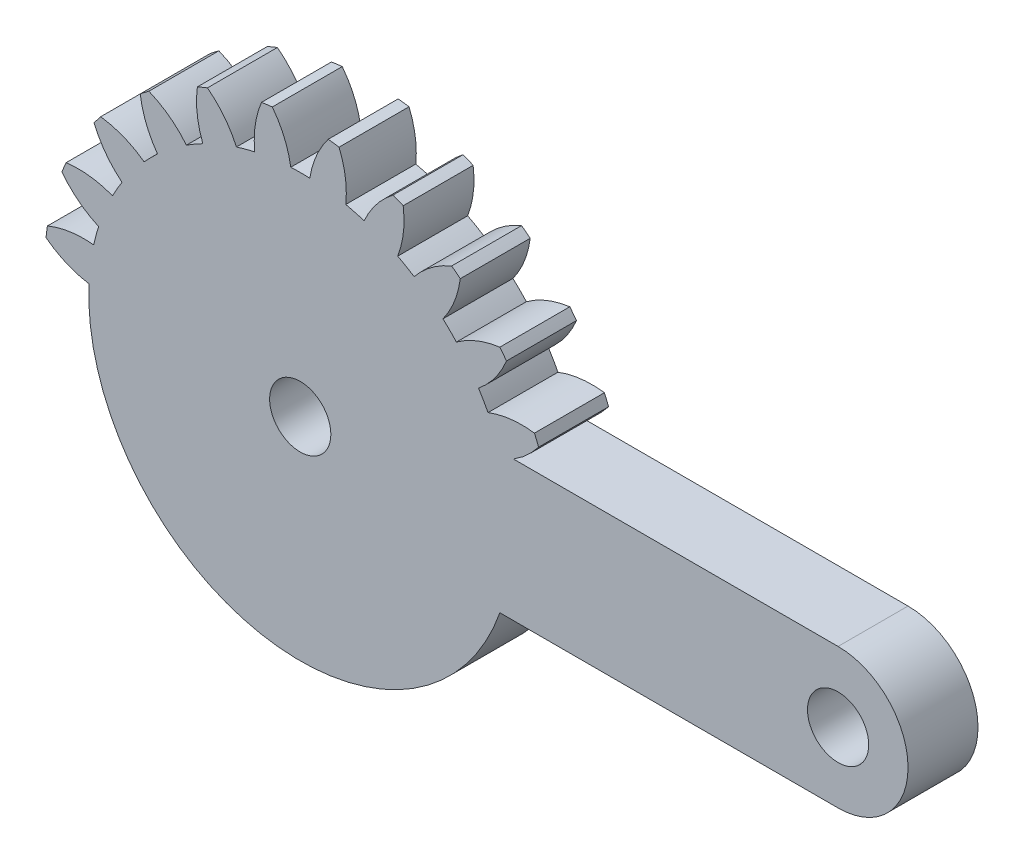
SolidWorks part; units mm, degrees
ref_plane "Front Plane" through (0, 0, 0) normal (0, 0, 1) x (1, 0, 0)
ref_plane "Top Plane" through (0, 0, 0) normal (0, 1, 0) x (1, 0, 0)
ref_plane "Right Plane" through (0, 0, 0) normal (1, 0, 0) x (0, 0, -1)
sketch "Sketch1" plane through (0, 0, 0) normal (0, 0, 1) x (1, 0, 0)
  line L0 (20.64, 4) -> (2.08, 4)
  line L1 (20.64, -4) -> (2.08, -4)
  circle A0 centre (-10.11, 0) radius 1.75
  circle A1 centre (20.64, 0) radius 1.75
  arc A2 (20.64, -4) -> (20.64, 4) centre (20.64, 0) ccw
  arc A6 (2.08, 4) -> (3.5201, 5.3071) centre (-0.7699, 8.5867) ccw
  arc A7 (3.5201, 5.3071) -> (3.2812, 5.8838) centre (-10.108, 0) ccw
  arc A8 (3.2812, 5.8838) -> (0.6255, 5.5703) centre (2.5667, 0.5313) ccw
  arc A9 (0.6255, 5.5703) -> (0.0827, 6.5103) centre (-10.108, 0) ccw
  arc A10 (0.0827, 6.5103) -> (1.6822, 8.6535) centre (-3.3105, 10.711) ccw
  arc A11 (1.6822, 8.6535) -> (1.3022, 9.1487) centre (-10.108, 0) ccw
  arc A12 (1.3022, 9.1487) -> (-1.182, 8.1585) centre (1.9973, 3.7936) ccw
  arc A13 (-1.182, 8.1585) -> (-1.9495, 8.926) centre (-10.108, 0) ccw
  arc A14 (-1.9495, 8.926) -> (-0.9593, 11.4102) centre (-6.3143, 12.1053) ccw
  arc A15 (-0.9593, 11.4102) -> (-1.4545, 11.7901) centre (-10.108, 0) ccw
  arc A16 (-1.4545, 11.7901) -> (-3.5977, 10.1907) centre (0.603, 6.7975) ccw
  arc A17 (-3.5977, 10.1907) -> (-4.5377, 10.7334) centre (-10.108, 0) ccw
  arc A18 (-4.5377, 10.7334) -> (-4.2242, 13.3892) centre (-9.5767, 12.6747) ccw
  arc A19 (-4.2242, 13.3892) -> (-4.8008, 13.6281) centre (-10.108, 0) ccw
  arc A20 (-4.8008, 13.6281) -> (-6.4571, 11.5285) centre (-1.5213, 9.3381) ccw
  arc A21 (-6.4571, 11.5285) -> (-7.5055, 11.8094) centre (-10.108, 0) ccw
  arc A22 (-7.5055, 11.8094) -> (-7.8901, 14.4558) centre (-12.8753, 12.3803) ccw
  arc A23 (-7.8901, 14.4558) -> (-8.5089, 14.5373) centre (-10.108, 0) ccw
  arc A24 (-8.5089, 14.5373) -> (-9.5653, 12.0806) centre (-4.2307, 11.2423) ccw
  arc A25 (-9.5653, 12.0806) -> (-10.6507, 12.0806) centre (-10.108, 0) ccw
  arc A26 (-10.6507, 12.0806) -> (-11.7071, 14.5373) centre (-15.9852, 11.2423) ccw
  arc A27 (-11.7071, 14.5373) -> (-12.3259, 14.4558) centre (-10.108, 0) ccw
  arc A28 (-12.3259, 14.4558) -> (-12.7104, 11.8094) centre (-7.3407, 12.3803) ccw
  arc A29 (-12.7104, 11.8094) -> (-13.7589, 11.5285) centre (-10.108, 0) ccw
  arc A30 (-13.7589, 11.5285) -> (-15.4151, 13.6281) centre (-18.6947, 9.3381) ccw
  arc A31 (-15.4151, 13.6281) -> (-15.9918, 13.3892) centre (-10.108, 0) ccw
  arc A32 (-15.9918, 13.3892) -> (-15.6783, 10.7334) centre (-10.6393, 12.6747) ccw
  arc A33 (-15.6783, 10.7334) -> (-16.6183, 10.1907) centre (-10.108, 0) ccw
  arc A34 (-16.6183, 10.1907) -> (-18.7615, 11.7901) centre (-20.819, 6.7975) ccw
  arc A35 (-18.7615, 11.7901) -> (-19.2567, 11.4102) centre (-10.108, 0) ccw
  arc A36 (-19.2567, 11.4102) -> (-18.2665, 8.926) centre (-13.9016, 12.1053) ccw
  arc A37 (-18.2665, 8.926) -> (-19.034, 8.1585) centre (-10.108, 0) ccw
  arc A38 (-19.034, 8.1585) -> (-21.5181, 9.1487) centre (-22.2133, 3.7936) ccw
  arc A39 (-21.5181, 9.1487) -> (-21.8981, 8.6535) centre (-10.108, 0) ccw
  arc A40 (-21.8981, 8.6535) -> (-20.2987, 6.5103) centre (-16.9054, 10.711) ccw
  arc A41 (-20.2987, 6.5103) -> (-20.8414, 5.5703) centre (-10.108, 0) ccw
  arc A42 (-20.8414, 5.5703) -> (-23.4972, 5.8838) centre (-22.7827, 0.5313) ccw
  arc A43 (-23.4972, 5.8838) -> (-23.7361, 5.3071) centre (-10.108, 0) ccw
  arc A44 (-23.7361, 5.3071) -> (-21.6364, 3.6509) centre (-19.446, 8.5867) ccw
  arc A45 (-21.6364, 3.6509) -> (-21.9174, 2.6025) centre (-10.108, 0) ccw
  arc A46 (-21.9174, 2.6025) -> (-24.5638, 2.2179) centre (-22.4883, -2.7673) ccw
  arc A47 (-24.5638, 2.2179) -> (-24.6453, 1.5991) centre (-10.108, 0) ccw
  arc A48 (-24.6453, 1.5991) -> (-22.1885, 0.5427) centre (-21.3503, 5.8773) ccw
  arc A49 (-22.1885, 0.5427) -> (-22.1885, -0.5427) centre (-10.108, 0) ccw
  arc A50 (-22.1885, -0.5427) -> (-24.6453, -1.5991) centre (-21.3503, -5.8773) ccw
  arc A51 (-24.6453, -1.5991) -> (-24.5638, -2.2179) centre (-10.108, 0) ccw
  arc A52 (-24.5638, -2.2179) -> (-21.9174, -2.6025) centre (-22.4883, 2.7673) ccw
  arc A53 (-21.9174, -2.6025) -> (-21.6364, -3.6509) centre (-10.108, 0) ccw
  arc A54 (-21.6364, -3.6509) -> (-23.7361, -5.3071) centre (-19.446, -8.5867) ccw
  arc A55 (-23.7361, -5.3071) -> (-23.4972, -5.8838) centre (-10.108, 0) ccw
  arc A56 (-23.4972, -5.8838) -> (-20.8414, -5.5703) centre (-22.7827, -0.5313) ccw
  arc A57 (-20.8414, -5.5703) -> (-20.2987, -6.5103) centre (-10.108, 0) ccw
  arc A58 (-20.2987, -6.5103) -> (-21.8981, -8.6535) centre (-16.9054, -10.711) ccw
  arc A59 (-21.8981, -8.6535) -> (-21.5181, -9.1487) centre (-10.108, 0) ccw
  arc A60 (-21.5181, -9.1487) -> (-19.034, -8.1585) centre (-22.2133, -3.7936) ccw
  arc A61 (-19.034, -8.1585) -> (-18.2665, -8.926) centre (-10.108, 0) ccw
  arc A62 (-18.2665, -8.926) -> (-19.2567, -11.4102) centre (-13.9016, -12.1053) ccw
  arc A63 (-19.2567, -11.4102) -> (-18.7615, -11.7901) centre (-10.108, 0) ccw
  arc A64 (-18.7615, -11.7901) -> (-16.6183, -10.1907) centre (-20.819, -6.7975) ccw
  arc A65 (-16.6183, -10.1907) -> (-15.6783, -10.7334) centre (-10.108, 0) ccw
  arc A66 (-15.6783, -10.7334) -> (-15.9918, -13.3892) centre (-10.6393, -12.6747) ccw
  arc A67 (-15.9918, -13.3892) -> (-15.4151, -13.6281) centre (-10.108, 0) ccw
  arc A68 (-15.4151, -13.6281) -> (-13.7589, -11.5285) centre (-18.6947, -9.3381) ccw
  arc A69 (-13.7589, -11.5285) -> (-12.7104, -11.8094) centre (-10.108, 0) ccw
  arc A70 (-12.7104, -11.8094) -> (-12.3259, -14.4558) centre (-7.3407, -12.3803) ccw
  arc A71 (-12.3259, -14.4558) -> (-11.7071, -14.5373) centre (-10.108, 0) ccw
  arc A72 (-11.7071, -14.5373) -> (-10.6507, -12.0806) centre (-15.9852, -11.2423) ccw
  arc A73 (-10.6507, -12.0806) -> (-9.5653, -12.0806) centre (-10.108, 0) ccw
  arc A74 (-9.5653, -12.0806) -> (-8.5089, -14.5373) centre (-4.2307, -11.2423) ccw
  arc A75 (-8.5089, -14.5373) -> (-7.8901, -14.4558) centre (-10.108, 0) ccw
  arc A76 (-7.8901, -14.4558) -> (-7.5055, -11.8094) centre (-12.8753, -12.3803) ccw
  arc A77 (-7.5055, -11.8094) -> (-6.4571, -11.5285) centre (-10.108, 0) ccw
  arc A78 (-6.4571, -11.5285) -> (-4.8008, -13.6281) centre (-1.5213, -9.3381) ccw
  arc A79 (-4.8008, -13.6281) -> (-4.2242, -13.3892) centre (-10.108, 0) ccw
  arc A80 (-4.2242, -13.3892) -> (-4.5377, -10.7334) centre (-9.5767, -12.6747) ccw
  arc A81 (-4.5377, -10.7334) -> (-3.5977, -10.1907) centre (-10.108, 0) ccw
  arc A82 (-3.5977, -10.1907) -> (-1.4545, -11.7901) centre (0.603, -6.7975) ccw
  arc A83 (-1.4545, -11.7901) -> (-0.9593, -11.4102) centre (-10.108, 0) ccw
  arc A84 (-0.9593, -11.4102) -> (-1.9495, -8.926) centre (-6.3143, -12.1053) ccw
  arc A85 (-1.9495, -8.926) -> (-1.182, -8.1585) centre (-10.108, 0) ccw
  arc A86 (-1.182, -8.1585) -> (1.3022, -9.1487) centre (1.9973, -3.7936) ccw
  arc A87 (1.3022, -9.1487) -> (1.6822, -8.6535) centre (-10.108, 0) ccw
  arc A88 (1.6822, -8.6535) -> (0.0827, -6.5103) centre (-3.3105, -10.711) ccw
  arc A89 (0.0827, -6.5103) -> (0.6255, -5.5703) centre (-10.108, 0) ccw
  arc A90 (0.6255, -5.5703) -> (3.2812, -5.8838) centre (2.5667, -0.5313) ccw
  arc A91 (3.2812, -5.8838) -> (3.5201, -5.3071) centre (-10.108, 0) ccw
  arc A92 (3.5201, -5.3071) -> (2.08, -4) centre (-0.7699, -8.5867) ccw
  dimension "D1" = 3.5
  dimension "D4" = 8
  dimension "D6" = 5.4
  dimension "D7" = 5.4
  dimension "D2" = 10.11
  dimension "D3" = 20.64
  dimension "D5" = 18.56
extrude "Boss-Extrude1" add sketch "Sketch1" along normal blind 4
sketch "Sketch2" plane through (0, 0, 4) normal (0, 0, 1) x (1, 0, 0)
  line L2 (20.64, 4) -> (2.08, 4)
  line L3 (2.08, -4) -> (20.64, -4)
  line L4 (20.64, 4) -> (2.08, 4)
  line L5 (1.3041, -4) -> (20.64, -4)
  arc A88 (20.64, -4) -> (20.64, 4) centre (20.64, 0) ccw
  arc A89 (2.08, 4) -> (3.5201, 5.3071) centre (-0.7699, 8.5867) ccw
  arc A90 (3.5201, 5.3071) -> (3.2812, 5.8838) centre (-10.108, 0) ccw
  arc A91 (3.2812, 5.8838) -> (0.6255, 5.5703) centre (2.5667, 0.5313) ccw
  arc A92 (0.6255, 5.5703) -> (0.0827, 6.5103) centre (-10.108, 0) ccw
  arc A93 (0.0827, 6.5103) -> (1.6822, 8.6535) centre (-3.3105, 10.711) ccw
  arc A94 (1.6822, 8.6535) -> (1.3022, 9.1487) centre (-10.108, 0) ccw
  arc A95 (1.3022, 9.1487) -> (-1.182, 8.1585) centre (1.9973, 3.7936) ccw
  arc A96 (-1.182, 8.1585) -> (-1.9495, 8.926) centre (-10.108, 0) ccw
  arc A97 (-1.9495, 8.926) -> (-0.9593, 11.4102) centre (-6.3143, 12.1053) ccw
  arc A98 (-0.9593, 11.4102) -> (-1.4545, 11.7901) centre (-10.108, 0) ccw
  arc A99 (-1.4545, 11.7901) -> (-3.5977, 10.1907) centre (0.603, 6.7975) ccw
  arc A100 (-3.5977, 10.1907) -> (-4.5377, 10.7334) centre (-10.108, 0) ccw
  arc A101 (-4.5377, 10.7334) -> (-4.2242, 13.3892) centre (-9.5767, 12.6747) ccw
  arc A102 (-4.2242, 13.3892) -> (-4.8008, 13.6281) centre (-10.108, 0) ccw
  arc A103 (-4.8008, 13.6281) -> (-6.4571, 11.5285) centre (-1.5213, 9.3381) ccw
  arc A104 (-6.4571, 11.5285) -> (-7.5055, 11.8094) centre (-10.108, 0) ccw
  arc A105 (-7.5055, 11.8094) -> (-7.8901, 14.4558) centre (-12.8753, 12.3803) ccw
  arc A106 (-7.8901, 14.4558) -> (-8.5089, 14.5373) centre (-10.108, 0) ccw
  arc A107 (-8.5089, 14.5373) -> (-9.5653, 12.0806) centre (-4.2307, 11.2423) ccw
  arc A108 (-9.5653, 12.0806) -> (-10.6507, 12.0806) centre (-10.108, 0) ccw
  arc A109 (-10.6507, 12.0806) -> (-11.7071, 14.5373) centre (-15.9852, 11.2423) ccw
  arc A110 (-11.7071, 14.5373) -> (-12.3259, 14.4558) centre (-10.108, 0) ccw
  arc A111 (-12.3259, 14.4558) -> (-12.7104, 11.8094) centre (-7.3407, 12.3803) ccw
  arc A112 (-12.7104, 11.8094) -> (-13.7589, 11.5285) centre (-10.108, 0) ccw
  arc A113 (-13.7589, 11.5285) -> (-15.4151, 13.6281) centre (-18.6947, 9.3381) ccw
  arc A114 (-15.4151, 13.6281) -> (-15.9918, 13.3892) centre (-10.108, 0) ccw
  arc A115 (-15.9918, 13.3892) -> (-15.6783, 10.7334) centre (-10.6393, 12.6747) ccw
  arc A116 (-15.6783, 10.7334) -> (-16.6183, 10.1907) centre (-10.108, 0) ccw
  arc A117 (-16.6183, 10.1907) -> (-18.7615, 11.7901) centre (-20.819, 6.7975) ccw
  arc A118 (-18.7615, 11.7901) -> (-19.2567, 11.4102) centre (-10.108, 0) ccw
  arc A119 (-19.2567, 11.4102) -> (-18.2665, 8.926) centre (-13.9016, 12.1053) ccw
  arc A120 (-18.2665, 8.926) -> (-19.034, 8.1585) centre (-10.108, 0) ccw
  arc A121 (-19.034, 8.1585) -> (-21.5181, 9.1487) centre (-22.2133, 3.7936) ccw
  arc A122 (-21.5181, 9.1487) -> (-21.8981, 8.6535) centre (-10.108, 0) ccw
  arc A123 (-21.8981, 8.6535) -> (-20.2987, 6.5103) centre (-16.9054, 10.711) ccw
  arc A124 (-20.2987, 6.5103) -> (-20.8414, 5.5703) centre (-10.108, 0) ccw
  arc A125 (-20.8414, 5.5703) -> (-23.4972, 5.8838) centre (-22.7827, 0.5313) ccw
  arc A126 (-23.4972, 5.8838) -> (-23.7361, 5.3071) centre (-10.108, 0) ccw
  arc A127 (-23.7361, 5.3071) -> (-21.6364, 3.6509) centre (-19.446, 8.5867) ccw
  arc A128 (-21.6364, 3.6509) -> (-21.9174, 2.6025) centre (-10.108, 0) ccw
  arc A129 (-21.9174, 2.6025) -> (-24.5638, 2.2179) centre (-22.4883, -2.7673) ccw
  arc A130 (-24.5638, 2.2179) -> (-24.6453, 1.5991) centre (-10.108, 0) ccw
  arc A131 (-24.6453, 1.5991) -> (-22.1885, 0.5427) centre (-21.3503, 5.8773) ccw
  arc A132 (-22.1885, 0.5427) -> (-22.1885, -0.5427) centre (-10.108, 0) ccw
  arc A133 (-22.1885, -0.5427) -> (-24.6453, -1.5991) centre (-21.3503, -5.8773) ccw
  arc A134 (-24.6453, -1.5991) -> (-24.5638, -2.2179) centre (-10.108, 0) ccw
  arc A135 (-24.5638, -2.2179) -> (-21.9174, -2.6025) centre (-22.4883, 2.7673) ccw
  arc A136 (-21.9174, -2.6025) -> (-21.6364, -3.6509) centre (-10.108, 0) ccw
  arc A137 (-21.6364, -3.6509) -> (-23.7361, -5.3071) centre (-19.446, -8.5867) ccw
  arc A138 (-23.7361, -5.3071) -> (-23.4972, -5.8838) centre (-10.108, 0) ccw
  arc A139 (-23.4972, -5.8838) -> (-20.8414, -5.5703) centre (-22.7827, -0.5313) ccw
  arc A140 (-20.8414, -5.5703) -> (-20.2987, -6.5103) centre (-10.108, 0) ccw
  arc A141 (-20.2987, -6.5103) -> (-21.8981, -8.6535) centre (-16.9054, -10.711) ccw
  arc A142 (-21.8981, -8.6535) -> (-21.5181, -9.1487) centre (-10.108, 0) ccw
  arc A143 (-21.5181, -9.1487) -> (-19.034, -8.1585) centre (-22.2133, -3.7936) ccw
  arc A144 (-19.034, -8.1585) -> (-18.2665, -8.926) centre (-10.108, 0) ccw
  arc A145 (-18.2665, -8.926) -> (-19.2567, -11.4102) centre (-13.9016, -12.1053) ccw
  arc A146 (-19.2567, -11.4102) -> (-18.7615, -11.7901) centre (-10.108, 0) ccw
  arc A147 (-18.7615, -11.7901) -> (-16.6183, -10.1907) centre (-20.819, -6.7975) ccw
  arc A148 (-16.6183, -10.1907) -> (-15.6783, -10.7334) centre (-10.108, 0) ccw
  arc A149 (-15.6783, -10.7334) -> (-15.9918, -13.3892) centre (-10.6393, -12.6747) ccw
  arc A150 (-15.9918, -13.3892) -> (-15.4151, -13.6281) centre (-10.108, 0) ccw
  arc A151 (-15.4151, -13.6281) -> (-13.7589, -11.5285) centre (-18.6947, -9.3381) ccw
  arc A152 (-13.7589, -11.5285) -> (-12.7104, -11.8094) centre (-10.108, 0) ccw
  arc A153 (-12.7104, -11.8094) -> (-12.3259, -14.4558) centre (-7.3407, -12.3803) ccw
  arc A154 (-12.3259, -14.4558) -> (-11.7071, -14.5373) centre (-10.108, 0) ccw
  arc A155 (-11.7071, -14.5373) -> (-10.6507, -12.0806) centre (-15.9852, -11.2423) ccw
  arc A156 (-10.6507, -12.0806) -> (-9.5653, -12.0806) centre (-10.108, 0) ccw
  arc A157 (-9.5653, -12.0806) -> (-8.5089, -14.5373) centre (-4.2307, -11.2423) ccw
  arc A158 (-8.5089, -14.5373) -> (-7.8901, -14.4558) centre (-10.108, 0) ccw
  arc A159 (-7.8901, -14.4558) -> (-7.5055, -11.8094) centre (-12.8753, -12.3803) ccw
  arc A160 (-7.5055, -11.8094) -> (-6.4571, -11.5285) centre (-10.108, 0) ccw
  arc A161 (-6.4571, -11.5285) -> (-4.8008, -13.6281) centre (-1.5213, -9.3381) ccw
  arc A162 (-4.8008, -13.6281) -> (-4.2242, -13.3892) centre (-10.108, 0) ccw
  arc A163 (-4.2242, -13.3892) -> (-4.5377, -10.7334) centre (-9.5767, -12.6747) ccw
  arc A164 (-4.5377, -10.7334) -> (-3.5977, -10.1907) centre (-10.108, 0) ccw
  arc A165 (-3.5977, -10.1907) -> (-1.4545, -11.7901) centre (0.603, -6.7975) ccw
  arc A166 (-1.4545, -11.7901) -> (-0.9593, -11.4102) centre (-10.108, 0) ccw
  arc A167 (-0.9593, -11.4102) -> (-1.9495, -8.926) centre (-6.3143, -12.1053) ccw
  arc A168 (-1.9495, -8.926) -> (-1.182, -8.1585) centre (-10.108, 0) ccw
  arc A169 (-1.182, -8.1585) -> (1.3022, -9.1487) centre (1.9973, -3.7936) ccw
  arc A170 (1.3022, -9.1487) -> (1.6822, -8.6535) centre (-10.108, 0) ccw
  arc A171 (1.6822, -8.6535) -> (0.0827, -6.5103) centre (-3.3105, -10.711) ccw
  arc A172 (0.0827, -6.5103) -> (0.6255, -5.5703) centre (-10.108, 0) ccw
  arc A173 (0.6255, -5.5703) -> (3.2812, -5.8838) centre (2.5667, -0.5313) ccw
  arc A174 (3.2812, -5.8838) -> (3.5201, -5.3071) centre (-10.108, 0) ccw
  arc A175 (3.5201, -5.3071) -> (2.08, -4) centre (-0.7699, -8.5867) ccw
  arc A176 (20.64, -4) -> (20.64, 4) centre (20.64, 0) ccw
  arc A177 (2.08, 4) -> (3.5201, 5.3071) centre (-0.7699, 8.5867) ccw
  arc A178 (3.5201, 5.3071) -> (3.2812, 5.8838) centre (-10.108, 0) ccw
  arc A179 (3.2812, 5.8838) -> (0.6255, 5.5703) centre (2.5667, 0.5313) ccw
  arc A180 (0.6255, -5.5703) -> (0.0827, 6.5103) centre (-10.108, 0) ccw
  arc A181 (0.0827, 6.5103) -> (1.6822, 8.6535) centre (-3.3105, 10.711) ccw
  arc A182 (1.6822, 8.6535) -> (1.3022, 9.1487) centre (-10.108, 0) ccw
  arc A183 (1.3022, 9.1487) -> (-1.182, 8.1585) centre (1.9973, 3.7936) ccw
  arc A184 (0.0827, 6.5103) -> (-3.5977, 10.1907) centre (-10.108, 0) ccw
  arc A185 (-1.9495, 8.926) -> (-0.9593, 11.4102) centre (-6.3143, 12.1053) ccw
  arc A186 (-0.9593, 11.4102) -> (-1.4545, 11.7901) centre (-10.108, 0) ccw
  arc A187 (-1.4545, 11.7901) -> (-3.5977, 10.1907) centre (0.603, 6.7975) ccw
  arc A188 (-3.5977, 10.1907) -> (-4.5377, 10.7334) centre (-10.108, 0) ccw
  arc A189 (-4.5377, 10.7334) -> (-4.2242, 13.3892) centre (-9.5767, 12.6747) ccw
  arc A190 (-4.2242, 13.3892) -> (-4.8008, 13.6281) centre (-10.108, 0) ccw
  arc A191 (-4.8008, 13.6281) -> (-6.4571, 11.5285) centre (-1.5213, 9.3381) ccw
  arc A192 (-4.5377, 10.7334) -> (-7.5055, 11.8094) centre (-10.108, 0) ccw
  arc A193 (-7.5055, 11.8094) -> (-7.8901, 14.4558) centre (-12.8753, 12.3803) ccw
  arc A194 (-7.8901, 14.4558) -> (-8.5089, 14.5373) centre (-10.108, 0) ccw
  arc A195 (-8.5089, 14.5373) -> (-9.5653, 12.0806) centre (-4.2307, 11.2423) ccw
  arc A196 (-7.5055, 11.8094) -> (-12.7104, 11.8094) centre (-10.108, 0) ccw
  arc A197 (-10.6507, 12.0806) -> (-11.7071, 14.5373) centre (-15.9852, 11.2423) ccw
  arc A198 (-11.7071, 14.5373) -> (-12.3259, 14.4558) centre (-10.108, 0) ccw
  arc A199 (-12.3259, 14.4558) -> (-12.7104, 11.8094) centre (-7.3407, 12.3803) ccw
  arc A200 (-12.7104, 11.8094) -> (-15.6783, 10.7334) centre (-10.108, 0) ccw
  arc A201 (-13.7589, 11.5285) -> (-15.4151, 13.6281) centre (-18.6947, 9.3381) ccw
  arc A202 (-15.4151, 13.6281) -> (-15.9918, 13.3892) centre (-10.108, 0) ccw
  arc A203 (-15.9918, 13.3892) -> (-15.6783, 10.7334) centre (-10.6393, 12.6747) ccw
  arc A204 (-15.6783, 10.7334) -> (-18.2665, 8.926) centre (-10.108, 0) ccw
  arc A205 (-16.6183, 10.1907) -> (-18.7615, 11.7901) centre (-20.819, 6.7975) ccw
  arc A206 (-18.7615, 11.7901) -> (-19.2567, 11.4102) centre (-10.108, 0) ccw
  arc A207 (-19.2567, 11.4102) -> (-18.2665, 8.926) centre (-13.9016, 12.1053) ccw
  arc A208 (-18.2665, 8.926) -> (-20.2987, 6.5103) centre (-10.108, 0) ccw
  arc A209 (-19.034, 8.1585) -> (-21.5181, 9.1487) centre (-22.2133, 3.7936) ccw
  arc A210 (-21.5181, 9.1487) -> (-21.8981, 8.6535) centre (-10.108, 0) ccw
  arc A211 (-21.8981, 8.6535) -> (-20.2987, 6.5103) centre (-16.9054, 10.711) ccw
  arc A212 (-20.2987, 6.5103) -> (-21.6364, 3.6509) centre (-10.108, 0) ccw
  arc A213 (-20.8414, 5.5703) -> (-23.4972, 5.8838) centre (-22.7827, 0.5313) ccw
  arc A214 (-23.4972, 5.8838) -> (-23.7361, 5.3071) centre (-10.108, 0) ccw
  arc A215 (-23.7361, 5.3071) -> (-21.6364, 3.6509) centre (-19.446, 8.5867) ccw
  arc A216 (-21.6364, 3.6509) -> (-22.1885, 0.5427) centre (-10.108, 0) ccw
  arc A217 (-21.9174, 2.6025) -> (-24.5638, 2.2179) centre (-22.4883, -2.7673) ccw
  arc A218 (-24.5638, 2.2179) -> (-24.6453, 1.5991) centre (-10.108, 0) ccw
  arc A219 (-24.6453, 1.5991) -> (-22.1885, 0.5427) centre (-21.3503, 5.8773) ccw
  arc A220 (-22.1885, 0.5427) -> (-21.9174, -2.6025) centre (-10.108, 0) ccw
  arc A221 (-22.1885, -0.5427) -> (-24.6453, -1.5991) centre (-21.3503, -5.8773) ccw
  arc A222 (-24.6453, -1.5991) -> (-24.5638, -2.2179) centre (-10.108, 0) ccw
  arc A223 (-24.5638, -2.2179) -> (-21.9174, -2.6025) centre (-22.4883, 2.7673) ccw
  arc A224 (-22.1885, -0.5427) -> (-21.6364, -3.6509) centre (-10.108, 0) ccw
  arc A225 (-21.6364, -3.6509) -> (-23.7361, -5.3071) centre (-19.446, -8.5867) ccw
  arc A226 (-23.7361, -5.3071) -> (-23.4972, -5.8838) centre (-10.108, 0) ccw
  arc A227 (-23.4972, -5.8838) -> (-20.8414, -5.5703) centre (-22.7827, -0.5313) ccw
  arc A228 (-21.6364, -3.6509) -> (-20.2987, -6.5103) centre (-10.108, 0) ccw
  arc A229 (-20.2987, -6.5103) -> (-21.8981, -8.6535) centre (-16.9054, -10.711) ccw
  arc A230 (-21.8981, -8.6535) -> (-21.5181, -9.1487) centre (-10.108, 0) ccw
  arc A231 (-21.5181, -9.1487) -> (-19.034, -8.1585) centre (-22.2133, -3.7936) ccw
  arc A232 (-20.2987, -6.5103) -> (-16.6183, -10.1907) centre (-10.108, 0) ccw
  arc A233 (-18.2665, -8.926) -> (-19.2567, -11.4102) centre (-13.9016, -12.1053) ccw
  arc A234 (-19.2567, -11.4102) -> (-18.7615, -11.7901) centre (-10.108, 0) ccw
  arc A235 (-18.7615, -11.7901) -> (-16.6183, -10.1907) centre (-20.819, -6.7975) ccw
  arc A236 (-16.6183, -10.1907) -> (-13.7589, -11.5285) centre (-10.108, 0) ccw
  arc A237 (-15.6783, -10.7334) -> (-15.9918, -13.3892) centre (-10.6393, -12.6747) ccw
  arc A238 (-15.9918, -13.3892) -> (-15.4151, -13.6281) centre (-10.108, 0) ccw
  arc A239 (-15.4151, -13.6281) -> (-13.7589, -11.5285) centre (-18.6947, -9.3381) ccw
  arc A240 (-13.7589, -11.5285) -> (-10.6507, -12.0806) centre (-10.108, 0) ccw
  arc A241 (-12.7104, -11.8094) -> (-12.3259, -14.4558) centre (-7.3407, -12.3803) ccw
  arc A242 (-12.3259, -14.4558) -> (-11.7071, -14.5373) centre (-10.108, 0) ccw
  arc A243 (-11.7071, -14.5373) -> (-10.6507, -12.0806) centre (-15.9852, -11.2423) ccw
  arc A244 (-12.7104, -11.8094) -> (-7.5055, -11.8094) centre (-10.108, 0) ccw
  arc A245 (-9.5653, -12.0806) -> (-8.5089, -14.5373) centre (-4.2307, -11.2423) ccw
  arc A246 (-8.5089, -14.5373) -> (-7.8901, -14.4558) centre (-10.108, 0) ccw
  arc A247 (-7.8901, -14.4558) -> (-7.5055, -11.8094) centre (-12.8753, -12.3803) ccw
  arc A248 (-7.5055, -11.8094) -> (-4.5377, -10.7334) centre (-10.108, 0) ccw
  arc A249 (-6.4571, -11.5285) -> (-4.8008, -13.6281) centre (-1.5213, -9.3381) ccw
  arc A250 (-4.8008, -13.6281) -> (-4.2242, -13.3892) centre (-10.108, 0) ccw
  arc A251 (-4.2242, -13.3892) -> (-4.5377, -10.7334) centre (-9.5767, -12.6747) ccw
  arc A252 (-4.5377, -10.7334) -> (-1.9495, -8.926) centre (-10.108, 0) ccw
  arc A253 (-3.5977, -10.1907) -> (-1.4545, -11.7901) centre (0.603, -6.7975) ccw
  arc A254 (-1.4545, -11.7901) -> (-0.9593, -11.4102) centre (-10.108, 0) ccw
  arc A255 (-0.9593, -11.4102) -> (-1.9495, -8.926) centre (-6.3143, -12.1053) ccw
  arc A256 (-1.9495, -8.926) -> (0.0827, -6.5103) centre (-10.108, 0) ccw
  arc A257 (-1.182, -8.1585) -> (1.3022, -9.1487) centre (1.9973, -3.7936) ccw
  arc A258 (1.3022, -9.1487) -> (1.6822, -8.6535) centre (-10.108, 0) ccw
  arc A259 (1.6822, -8.6535) -> (0.0827, -6.5103) centre (-3.3105, -10.711) ccw
  arc A260 (0.0827, -6.5103) -> (0.6255, -5.5703) centre (-10.108, 0) ccw
  arc A261 (0.6255, -5.5703) -> (3.2812, -5.8838) centre (2.5667, -0.5313) ccw
  arc A262 (3.2812, -5.8838) -> (3.5201, -5.3071) centre (-10.108, 0) ccw
  arc A263 (3.5201, -5.3071) -> (2.08, -4) centre (-0.7699, -8.5867) ccw
  dimension "D1" = 0
extrude "Cut-Extrude1" cut sketch "Sketch2" against normal through all contours A262 A263 L5 A180 A261 | A258 A259 A256 A257 | A254 A255 A252 A253 | A250 A251 A248 A249 | A246 A247 A244 A245 | A242 A243 A240 A241 | A238 A239 A236 A237 | A234 A235 A232 A233 | A232 A229 A230 A231 | A228 A225 A226 A227 | A222 A223 A220 A221
